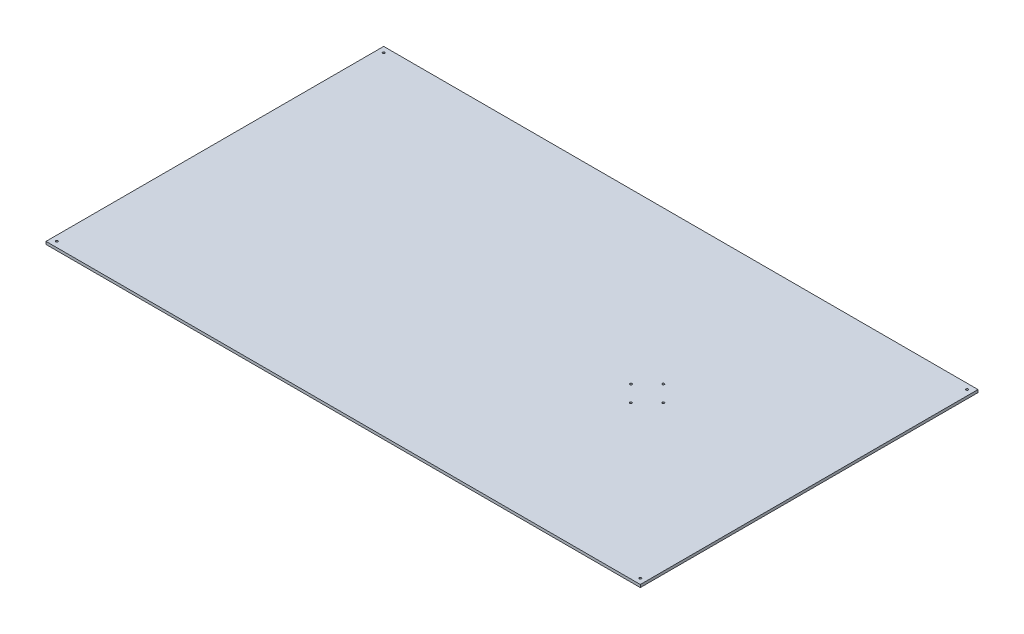
SolidWorks part; units mm, degrees
ref_plane "前视基准面" through (0, 0, 0) normal (0, 0, 1) x (1, 0, 0)
ref_plane "上视基准面" through (0, 0, 0) normal (0, 1, 0) x (1, 0, 0)
ref_plane "右视基准面" through (0, 0, 0) normal (1, 0, 0) x (0, 0, -1)
sketch "草图2" plane through (0, 0, 0) normal (0, 1, 0) x (1, 0, 0)
  line L0 (0, 863.8843) -> (0, -975.072) construction
  line L1 (-1426.8019, 0) -> (1553.6216, 0) construction
  line L2 (-1100, 625) -> (1100, 625)
  line L3 (-1100, -625) -> (1100, -625)
  line L4 (-1100, 625) -> (-1100, -625)
  line L5 (1100, 625) -> (1100, -625)
  line L6 (480, 163.4279) -> (480, -180.4687) construction
  circle A1 centre (480, 0) radius 60
  dimension "D1" = 620
  dimension "D3" = 2200
  dimension "D4" = 1250
extrude "凸台-拉伸1" add sketch "草图2" along normal blind 10 contours L4 L3 L5 L2
sketch "草图3" plane through (0, 10, 0) normal (0, 1, 0) x (1, 0, 0)
  line L0 (-1100, 625) -> (1100, 625) construction
  line L1 (-1080, 605) -> (1080, 605)
  line L2 (-1080, 605) -> (-1080, -605)
  line L3 (-1080, -605) -> (1080, -605)
  line L4 (1080, 605) -> (1080, -605)
  line L5 (-1100, 625) -> (-1100, -625) construction
  line L6 (-1100, -625) -> (1100, -625) construction
  line L7 (1100, 625) -> (1100, -625) construction
  dimension "D1" = 20
  dimension "D2" = 20
  dimension "D3" = 20
  dimension "D4" = 20
hole_wizard "大小mm 暗销孔1" positions "3D草图1" profile "草图4" hole size "Ø8.0" standard "ISO"
sketch3d "3D草图1"
  point P0 (-1080, 10, -605)
  point P3 (1080, 10, -605)
  point P6 (1080, 10, 605)
  point P9 (-1080, 10, 605)
sketch "草图4" plane through (-1080, 10, -605) normal (1, 0, 0) x (0, 0, 1)
  line L0 (0, 0) -> (0, 22.4034)
  line L1 (0, 22.4034) -> (4, 20)
  line L2 (4, 20) -> (4, 0)
  line L5 (4, 0) -> (0, 0)
  line L10 (0, 22.4034) -> (-4, 20) construction
  line L11 (0, -6.35) -> (0, 107.95) construction
  dimension "孔直径" = 8
  dimension "孔深度" = 20
  dimension "导头角度" = 118
sketch "草图5" plane through (0, 10, 0) normal (0, 1, 0) x (1, 0, 0)
  line L0 (-1277.4468, 0) -> (1241.3671, 0) construction
  line L1 (500, 279.6177) -> (500, -245.7929) construction
  line L2 (1100, 625) -> (1100, -625) construction
  circle A0 centre (500, 0) radius 60
  dimension "D2" = 120
  dimension "D1" = 600
hole_wizard "大小mm 暗销孔2" positions "3D草图2" profile "草图6" hole size "Ø8.0" standard "ISO"
sketch3d "3D草图2"
  line L0 (500, 10, -279.6177) -> (500, 10, 245.7929) construction
  line L1 (-1277.4468, 10, 0) -> (1241.3671, 10, 0) construction
  circle A0 centre (500, 10, 0) radius 60 construction
  point P0 (500, 10, -60)
  point P4 (500, 70, 0)
  point P7 (440, 10, 0)
  point P11 (500, 10, 60)
  point P13 (560, 10, 0)
sketch "草图6" plane through (500, 10, -60) normal (1, 0, 0) x (0, 0, 1)
  line L0 (0, 0) -> (0, 22.4034)
  line L1 (0, 22.4034) -> (4, 20)
  line L2 (4, 20) -> (4, 0)
  line L5 (4, 0) -> (0, 0)
  line L10 (0, 22.4034) -> (-4, 20) construction
  line L11 (0, -6.35) -> (0, 107.95) construction
  dimension "孔直径" = 8
  dimension "孔深度" = 20
  dimension "导头角度" = 118
